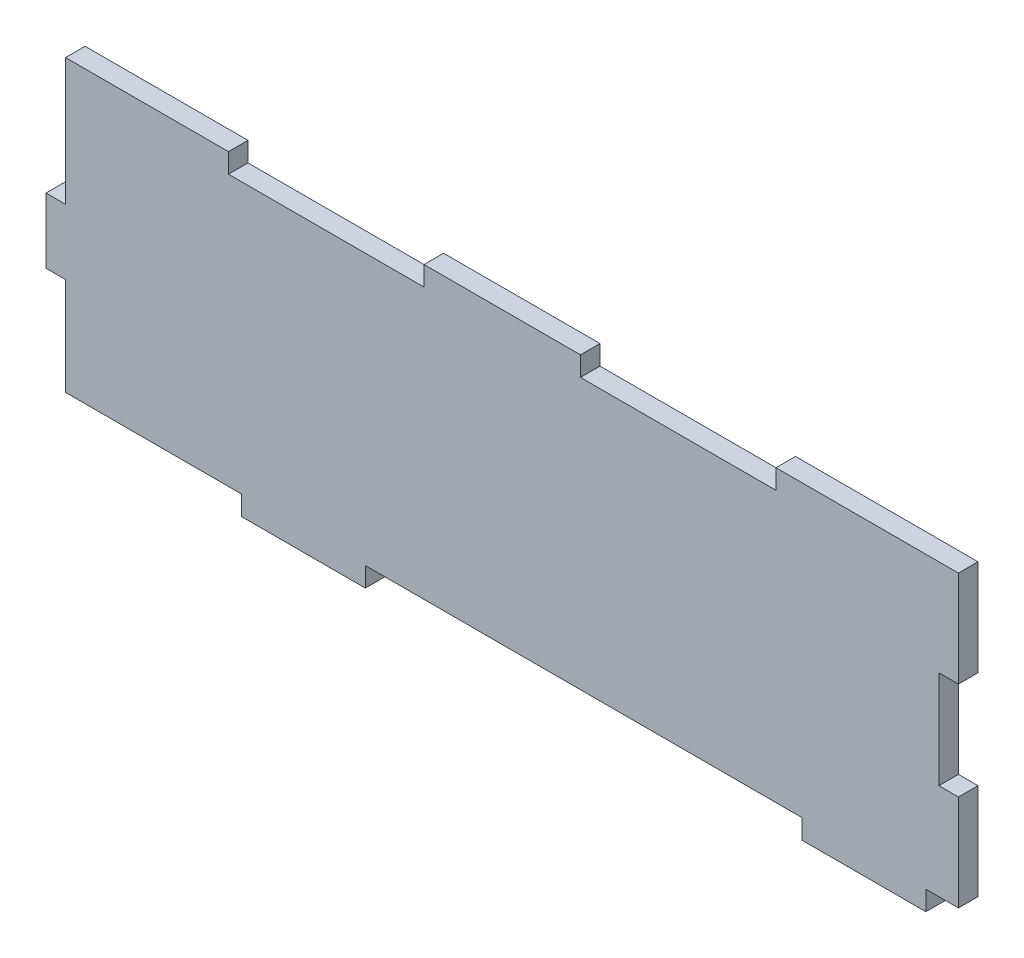
SolidWorks part; units mm, degrees
ref_plane "Plan de face" through (0, 0, 0) normal (0, 0, 1) x (1, 0, 0)
ref_plane "Plan de dessus" through (0, 0, 0) normal (0, 1, 0) x (1, 0, 0)
ref_plane "Plan de droite" through (0, 0, 0) normal (1, 0, 0) x (0, 0, -1)
sketch "Esquisse1" plane through (0, 0, 0) normal (0, 0, 1) x (1, 0, 0)
  line L1 (0, 0) -> (-330, 0)
  line L2 (0, 0) -> (0, 75)
  line L3 (0, 75) -> (-330, 75)
  line L4 (-330, 0) -> (-330, 75)
  dimension "D1" = 330
  dimension "D2" = 75
extrude "Boss.-Extru.1" add sketch "Esquisse1" along normal blind 6
sketch "Esquisse2" plane through (0, 0, 6) normal (0, 0, 1) x (1, 0, 0)
  line L0 (-330, 0) -> (0, 0) construction
  line L1 (-330, 0) -> (-270, 0)
  line L2 (-330, 36) -> (-330, 0)
  line L3 (-324, 6) -> (-270, 6)
  line L4 (-270, 0) -> (-270, 6)
  line L5 (0, 0) -> (-60, 0)
  line L6 (0, 26) -> (0, 0)
  line L7 (-6, 6) -> (-60, 6)
  line L8 (-60, 0) -> (-60, 6)
  line L9 (-232, 0) -> (-98, 0)
  line L10 (-232, 0) -> (-232, 6)
  line L11 (-232, 6) -> (-98, 6)
  line L12 (-98, 0) -> (-98, 6)
  line L16 (-330, 36) -> (-324, 36)
  line L17 (-324, 6) -> (-324, 36)
  line L18 (-330, 75) -> (-324, 75)
  line L19 (-330, 75) -> (-330, 56)
  line L20 (-330, 56) -> (-324, 56)
  line L21 (-324, 75) -> (-324, 56)
  line L22 (0, 75) -> (-6, 75)
  line L23 (0, 75) -> (0, 46)
  line L24 (0, 46) -> (-6, 46)
  line L25 (-6, 75) -> (-6, 46)
  line L28 (0, 26) -> (-6, 26)
  line L29 (-6, 6) -> (-6, 26)
  dimension "D2" = 6
  dimension "D3" = 6
  dimension "D4" = 134
  dimension "D5" = 38
  dimension "D6" = 38
  dimension "D7" = 6
  dimension "D8" = 20
  dimension "D9" = 30
  dimension "D10" = 6
  dimension "D11" = 6
  dimension "D12" = 60
  dimension "D13" = 20
  dimension "D14" = 6
  dimension "D15" = 6
  dimension "D16" = 20
extrude "Enlèv. mat.-Extru.1" cut sketch "Esquisse2" against normal blind 6
sketch "Esquisse3" plane through (0, 75, 0) normal (0, 1, 0) x (1, 0, 0)
  line L0 (-6, -6) -> (-324, -6) construction
  line L6 (-6, 0) -> (-56, 0)
  line L7 (-6, 0) -> (-6, -6)
  line L8 (-6, -6) -> (-56, -6)
  line L9 (-56, 0) -> (-56, -6)
  dimension "D2" = 50
extrude "Boss.-Extru.2" add sketch "Esquisse3" along normal blind 70
sketch "Esquisse5" plane through (-6, 0, 0) normal (1, 0, 0) x (0, 0, -1)
  line L0 (-6, 145) -> (-6, 46) construction
  line L1 (-6, 85) -> (0, 85)
  line L2 (-6, 85) -> (-6, 125)
  line L3 (-6, 125) -> (0, 125)
  line L4 (0, 85) -> (0, 125)
  line L5 (0, 145) -> (0, 46) construction
  line L8 (-6, 145) -> (0, 145) construction
  dimension "D1" = 40
  dimension "D2" = 20
extrude "Boss.-Extru.3" add sketch "Esquisse5" along normal blind 6
sketch "Esquisse6" plane through (0, 75, 0) normal (0, 1, 0) x (1, 0, 0)
  line L1 (-56, -6) -> (-324, -6)
  line L2 (-56, -6) -> (-56, 0)
  line L3 (-56, 0) -> (-324, 0)
  line L4 (-324, -6) -> (-324, 0)
extrude "Boss.-Extru.4" add sketch "Esquisse6" along normal blind 20
sketch "Esquisse7" plane through (0, 0, 6) normal (0, 0, 1) x (1, 0, 0)
  line L0 (-324, 95) -> (-56, 95) construction
  line L1 (-56, 145) -> (2.2706, 145)
  line L2 (-56, 145) -> (-56, -3.0894)
  line L3 (-56, -3.0894) -> (2.2706, -3.0894)
  line L4 (2.2706, 145) -> (2.2706, -3.0894)
  line L5 (-106, 95) -> (-166, 95)
  line L6 (-106, 95) -> (-106, 89)
  line L7 (-106, 89) -> (-166, 89)
  line L8 (-166, 95) -> (-166, 89)
  line L9 (-324, 56) -> (-324, 95) construction
  line L10 (-214, 95) -> (-274, 95)
  line L11 (-214, 95) -> (-214, 89)
  line L12 (-214, 89) -> (-274, 89)
  line L13 (-274, 95) -> (-274, 89)
  dimension "D1" = 6
  dimension "D2" = 60
  dimension "D3" = 60
  dimension "D4" = 6
  dimension "D5" = 50
  dimension "D6" = 50
extrude "Enlèv. mat.-Extru.3" cut sketch "Esquisse7" against normal through all
sketch "Esquisse8" plane through (-56, 0, 0) normal (1, 0, 0) x (0, 0, -1)
  line L1 (0, 95) -> (0, 6) construction
  line L2 (-6, 6) -> (0, 6)
  line L3 (-6, 6) -> (-6, 35.5)
  line L4 (-6, 35.5) -> (0, 35.5)
  line L6 (0, 6) -> (0, 35.5)
  line L8 (-6, 95) -> (0, 95)
  line L9 (-6, 95) -> (-6, 65.5)
  line L10 (-6, 65.5) -> (0, 65.5)
  line L11 (0, 95) -> (0, 65.5)
  dimension "D1" = 30
  dimension "D2" = 29.5
extrude "Boss.-Extru.5" add sketch "Esquisse8" along normal blind 6
